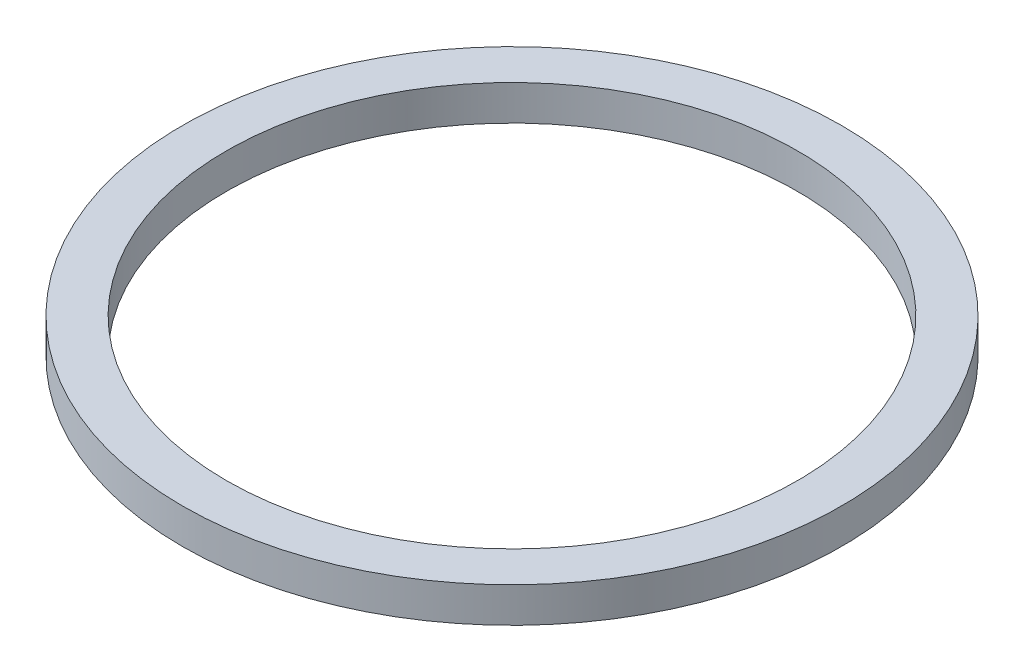
SolidWorks part; units mm, degrees
ref_plane "Front Plane" through (0, 0, 0) normal (0, 0, 1) x (1, 0, 0)
ref_plane "Top Plane" through (0, 0, 0) normal (0, 1, 0) x (1, 0, 0)
ref_plane "Right Plane" through (0, 0, 0) normal (1, 0, 0) x (0, 0, -1)
sketch "Sketch1" plane through (0, 0, 0) normal (0, 1, 0) x (1, 0, 0)
  circle A0 centre (0, 0) radius 23.8125
  circle A1 centre (0, 0) radius 20.6375
extrude "Boss-Extrude1" add sketch "Sketch1" along normal blind 2.54
